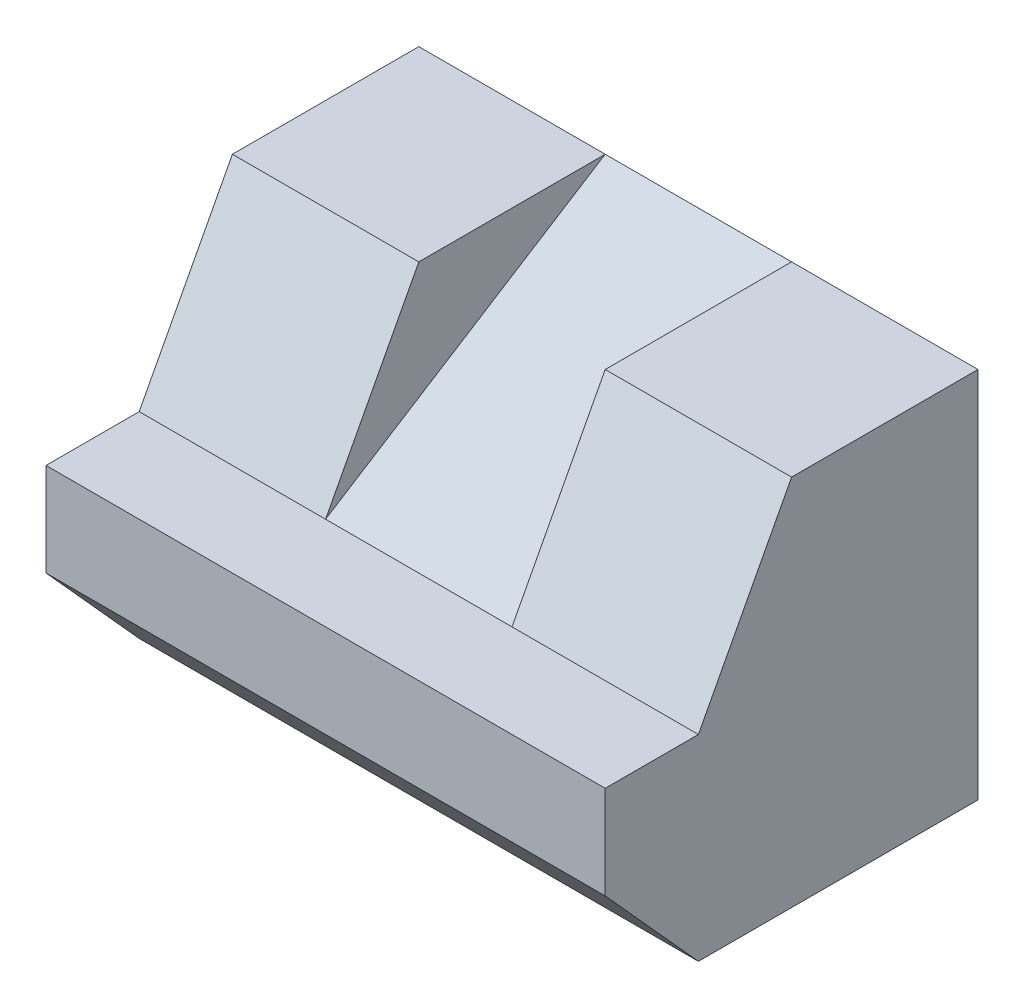
SolidWorks part; units mm, degrees
material "6061 Alloy"
ref_plane "Front Plane" through (0, 0, 0) normal (0, 0, 1) x (1, 0, 0)
ref_plane "Top Plane" through (0, 0, 0) normal (0, 1, 0) x (1, 0, 0)
ref_plane "Right Plane" through (0, 0, 0) normal (1, 0, 0) x (0, 0, -1)
sketch "Croquis1" plane through (0, 0, 0) normal (1, 0, 0) x (0, 0, -1)
  line L0 (0, 0) -> (0, 50.8)
  line L1 (0, 50.8) -> (-25.4, 50.8)
  line L2 (-25.4, 50.8) -> (-38.1, 26.7759)
  line L3 (-38.1, 26.7759) -> (-50.8, 26.7759)
  line L4 (-50.8, 26.7759) -> (-50.8, 14.0759)
  line L5 (-50.8, 14.0759) -> (-38.1, 0)
  line L6 (-38.1, 0) -> (0, 0)
  point P3 (-50.8, 27.867)
  point P9 (-50.8, 26.7526)
  point P10 (-38.1, 26.7759)
  point P11 (0, 0)
  dimension "D1" = 25.4
  dimension "D2" = 50.8
  dimension "D3" = 38.1
  dimension "D4" = 12.7
  dimension "D5" = 50.8
extrude "Saliente-Extruir1" add sketch "Croquis1" along normal blind 76.2
sketch "Croquis2" plane through (76.2, 0, 0) normal (1, 0, 0) x (0, 0, -1)
  line L0 (-38.1, 26.7759) -> (0, 50.8)
  line L6 (-25.4, 50.8) -> (-38.1, 26.7759)
  line L7 (0, 50.8) -> (-25.4, 50.8)
  line L8 (-25.4, 50.8) -> (-38.1, 26.7759)
  line L9 (0, 50.8) -> (-25.4, 50.8)
  dimension "D1" = 0
extrude "Cortar-Extruir1" cut sketch "Croquis2" against normal blind 25.4 from offset 25.4
